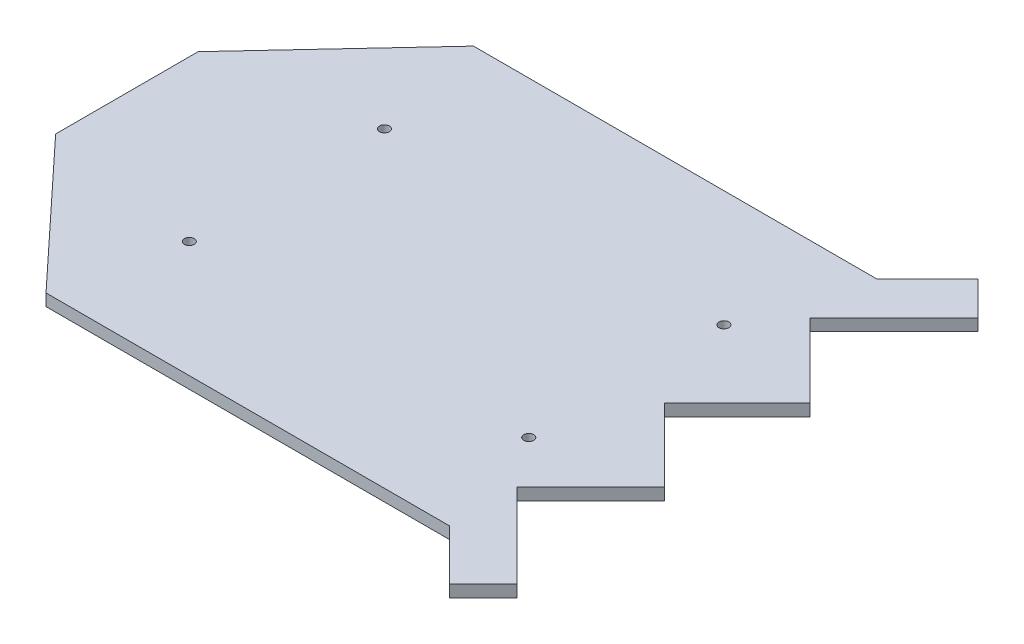
SolidWorks part; units mm, degrees
ref_plane "Front Plane" through (0, 0, 0) normal (0, 0, 1) x (1, 0, 0)
ref_plane "Top Plane" through (0, 0, 0) normal (0, 1, 0) x (1, 0, 0)
ref_plane "Right Plane" through (0, 0, 0) normal (1, 0, 0) x (0, 0, -1)
sketch "Sketch1" plane through (0, 0, 0) normal (0, 1, 0) x (1, 0, 0)
  line L0 (-95.1639, 0) -> (91.7213, 0) construction
  line L1 (0, -30) -> (0, 30)
  line L2 (0, 30) -> (55.94, 90)
  line L3 (55.94, 90) -> (225.94, 90)
  line L4 (225.94, 90) -> (247.1532, 111.2132)
  line L5 (247.1532, 111.2132) -> (261.2953, 97.0711)
  line L6 (261.2953, 97.0711) -> (225.94, 61.7157)
  line L7 (225.94, 61.7157) -> (256.9657, 30.69)
  line L8 (256.9657, 30.69) -> (225.94, -0.3824)
  line L9 (256.9657, -30.69) -> (225.94, 0.3824)
  line L10 (225.94, -61.7157) -> (256.9657, -30.69)
  line L11 (261.2953, -97.0711) -> (225.94, -61.7157)
  line L12 (247.1532, -111.2132) -> (261.2953, -97.0711)
  line L13 (225.94, -90) -> (247.1532, -111.2132)
  line L14 (55.94, -90) -> (225.94, -90)
  line L15 (0, -30) -> (55.94, -90)
  point P21 (0, 0)
  dimension "D1" = 30
  dimension "D2" = 90
  dimension "D3" = 170
  dimension "D4" = 30
  dimension "D5" = 20
  dimension "D6" = 170
  dimension "D7" = 170
  dimension "D8" = 50
  dimension "D9" = 30.69
  dimension "D10" = 43.91
  dimension "D11" = 55.94
extrude "Boss-Extrude1" add sketch "Sketch1" along normal blind 5
sketch "Sketch2" plane through (0, 5, 0) normal (0, 1, 0) x (1, 0, 0)
  line L0 (55.94, 90) -> (225.94, 90) construction
  line L1 (220.29, 76.81) -> (200.29, 76.81)
  line L2 (220.29, 76.81) -> (220.29, 56.81)
  line L3 (220.29, 56.81) -> (200.29, 56.81)
  line L4 (200.29, 76.81) -> (200.29, 56.81)
  line L5 (-17.3221, 0) -> (25.7084, 0) construction
  line L6 (200.29, -76.81) -> (200.29, -56.81)
  line L7 (220.29, -56.81) -> (200.29, -56.81)
  line L8 (220.29, -76.81) -> (220.29, -56.81)
  line L9 (220.29, -76.81) -> (200.29, -76.81)
  circle A0 centre (210.29, 66.81) radius 2.1
  circle A1 centre (210.29, 41.08) radius 2.1
  circle A2 centre (210.29, -41.08) radius 2.1
  circle A3 centre (210.29, -66.81) radius 2.1
  point P22 (0, 0)
  dimension "D6" = 4.2
  dimension "D7" = 4.2
  dimension "D8" = 10
  dimension "D9" = 10
  dimension "D1" = 13.19
  dimension "D2" = 144.35
  dimension "D3" = 20
  dimension "D4" = 20
  dimension "D5" = 48.92
extrude "Cut-Extrude1" cut sketch "Sketch2" against normal blind 5 contours A1 | A2
sketch "Sketch3" plane through (0, 5, 0) normal (0, 1, 0) x (1, 0, 0)
  line L0 (200.29, 76.81) -> (200.29, 56.81) construction
  line L1 (57.31, 76.81) -> (77.31, 76.81)
  line L2 (57.31, 76.81) -> (57.31, 56.81)
  line L3 (57.31, 56.81) -> (77.31, 56.81)
  line L4 (77.31, 76.81) -> (77.31, 56.81)
  line L5 (57.31, -76.81) -> (77.31, -76.81)
  line L6 (57.31, -76.81) -> (57.31, -56.81)
  line L7 (57.31, -56.81) -> (77.31, -56.81)
  line L8 (77.31, -76.81) -> (77.31, -56.81)
  line L9 (200.29, -76.81) -> (200.29, -56.81) construction
  circle A0 centre (67.37, 41.08) radius 2.1
  circle A1 centre (67.36, -41.08) radius 2.1
  circle A3 centre (210.29, 41.08) radius 2.1 construction
  circle A4 centre (210.29, -41.08) radius 2.1 construction
  circle A5 centre (67.31, 66.81) radius 2.1
  circle A6 centre (67.31, -66.81) radius 2.1
  point P24 (0, 0)
  dimension "D7" = 4.2
  dimension "D8" = 4.2
  dimension "D9" = 142.92
  dimension "D10" = 142.93
  dimension "D11" = 4.2
  dimension "D12" = 4.2
  dimension "D13" = 10
  dimension "D14" = 10
  dimension "D15" = 10
  dimension "D16" = 10
  dimension "D1" = 20
  dimension "D2" = 20
  dimension "D3" = 20
  dimension "D4" = 20
  dimension "D5" = 122.98
  dimension "D6" = 122.98
sketch "Sketch5" plane through (0, 5, 0) normal (0, 1, 0) x (1, 0, 0)
  circle A0 centre (67.37, 41.08) radius 2.1
  circle A1 centre (67.36, -41.08) radius 2.1
extrude "Cut-Extrude4" cut sketch "Sketch5" against normal blind 10 contours A0 | A1
